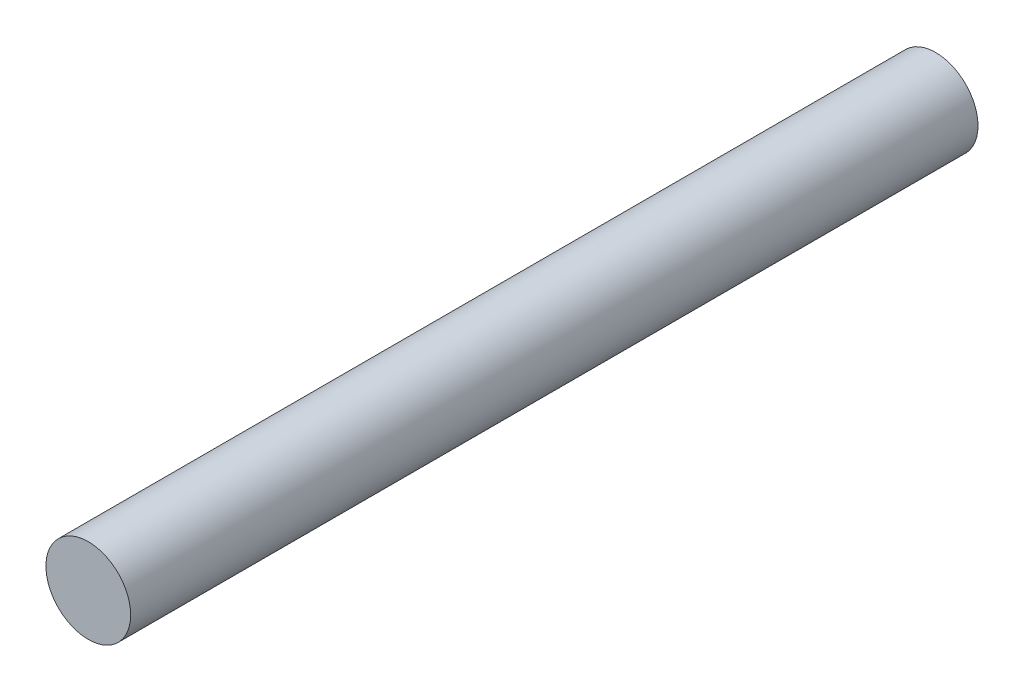
SolidWorks part; units mm, degrees
material "ABS"
ref_plane "Front Plane" through (0, 0, 0) normal (0, 0, 1) x (1, 0, 0)
ref_plane "Top Plane" through (0, 0, 0) normal (0, 1, 0) x (1, 0, 0)
ref_plane "Right Plane" through (0, 0, 0) normal (1, 0, 0) x (0, 0, -1)
sketch "Pin Profile" plane through (0, 0, 0) normal (0, 0, 1) x (1, 0, 0)
  circle A0 centre (0, 0) radius 0.5
  dimension "D1" = 1
extrude "Pin Extrude" add sketch "Pin Profile" along normal blind 10
